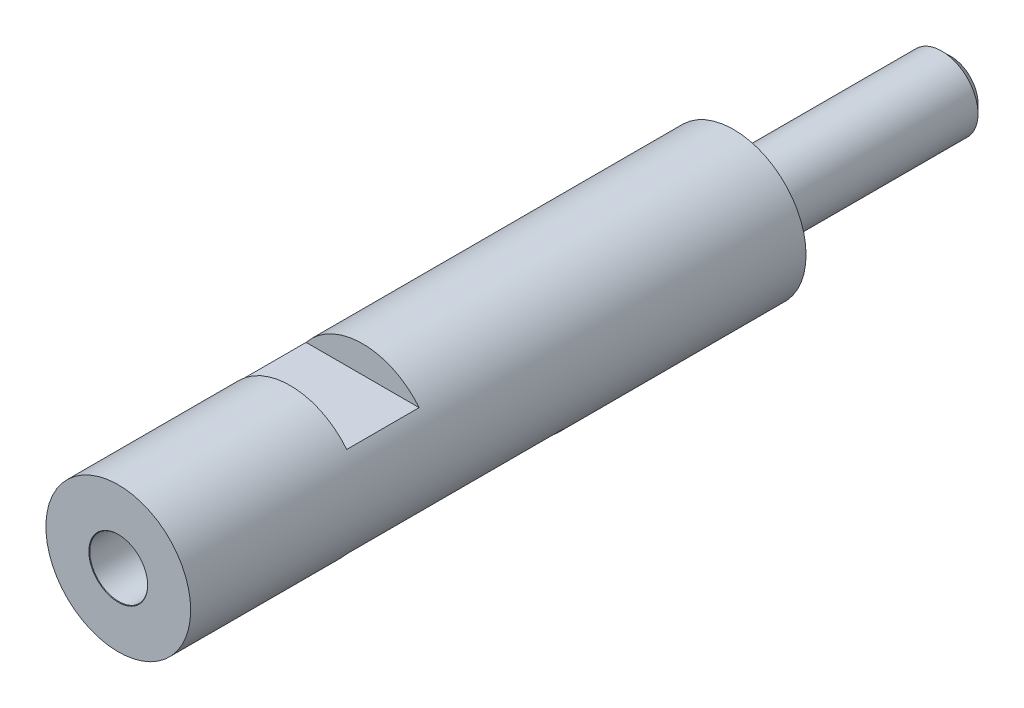
SolidWorks part; units mm, degrees
ref_plane "Front Plane" through (0, 0, 0) normal (0, 0, 1) x (1, 0, 0)
ref_plane "Top Plane" through (0, 0, 0) normal (0, 1, 0) x (1, 0, 0)
ref_plane "Right Plane" through (0, 0, 0) normal (1, 0, 0) x (0, 0, -1)
sketch "Sketch1" plane through (0, 0, 0) normal (0, 0, 1) x (1, 0, 0)
  circle A0 centre (0, 0) radius 2
  dimension "D1" = 4
extrude "Boss-Extrude3" add sketch "Sketch1" against normal blind 12 contours A0
sketch "Sketch3" plane through (0, 0, 0) normal (0, 0, 1) x (1, 0, 0)
  circle A0 centre (0, 0) radius 4
  dimension "D1" = 8
extrude "Boss-Extrude4" add sketch "Sketch3" along normal blind 34
sketch "Sketch4" plane through (0, 0, 0) normal (1, 0, 0) x (0, 0, -1)
  line L0 (-24.5, 4) -> (-20.5, 4)
  line L1 (0, 4) -> (-34, 4) construction
  line L2 (-24.5, -4) -> (-12.5, -4)
  line L3 (-34, -4) -> (0, -4) construction
  line L4 (-24.5, 4) -> (-24.5, 2.5)
  line L5 (-24.5, 2.5) -> (-20.5, 2.5)
  line L7 (-24.5, -4) -> (-24.5, -2.5)
  line L8 (-24.5, -2.5) -> (-12.5, -2.5)
  line L9 (-12.5, -2.5) -> (-12.5, -4)
  line L11 (-20.5, 2.5) -> (-20.5, 4)
  dimension "D1" = 1.5
  dimension "D2" = 12
  dimension "D3" = 9.5
  dimension "D4" = 1.5
extrude "Cut-Extrude1" cut sketch "Sketch4" against normal mid plane 34 contours L11 L0 L4 L5 | L9 L2 L7 L8
sketch "Sketch6" plane through (0, 0, 34) normal (0, 0, 1) x (1, 0, 0)
  point P0 (0, 0)
hole_wizard "Ø3.2 (3.2) Diameter Hole1" positions "Sketch6" profile "Sketch7" hole size "Ø3.2" standard "ANSI Metric"
sketch "Sketch7" plane through (0, 0, 34) normal (1, 0, 0) x (0, -1, 0)
  line L0 (0, 0) -> (0, 14.9614)
  line L1 (0, 14.9614) -> (1.6, 14)
  line L2 (1.6, 14) -> (1.6, 0.025)
  line L3 (1.6, 0.025) -> (1.625, 0)
  line L5 (1.625, 0) -> (0, 0)
  line L6 (-1.6, 0.025) -> (-1.625, 0) construction
  line L10 (0, 14.9614) -> (-1.6, 14) construction
  line L11 (0, -6.35) -> (0, 107.95) construction
  dimension "Hole Dia." = 3.2
  dimension "Hole Depth" = 14
  dimension "Near C'Sink Dia." = 3.25
  dimension "Near C'Sink Angle" = 90
  dimension "Drill Angle" = 118
chamfer "Chamfer1" distance 0.5 angle 45 1 edges at (2, 0, -12)
equation "\"0.5.00mm\"=10"
